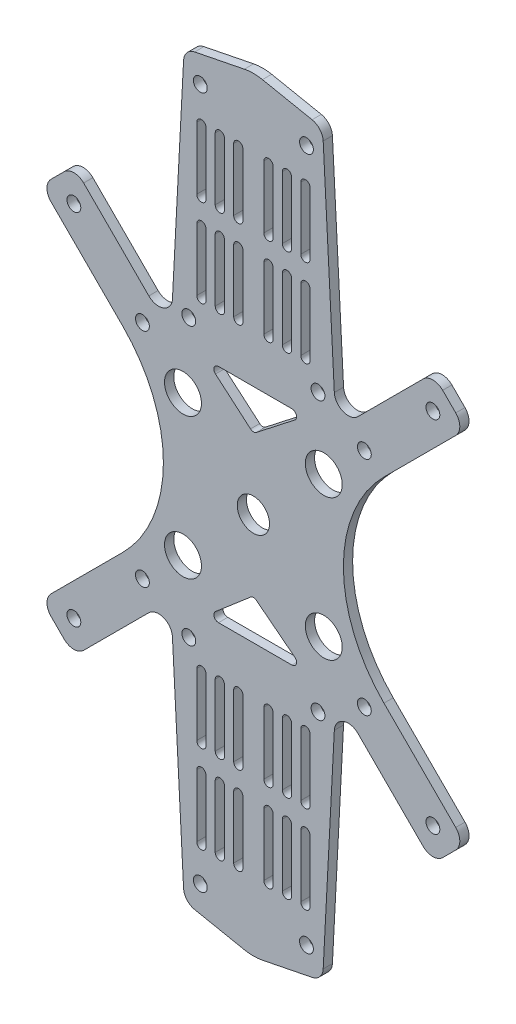
SolidWorks part; units mm, degrees
ref_plane "Alzado" through (0, 0, 0) normal (0, 0, 1) x (1, 0, 0)
ref_plane "Planta" through (0, 0, 0) normal (0, 1, 0) x (1, 0, 0)
ref_plane "Vista lateral" through (0, 0, 0) normal (1, 0, 0) x (0, 0, -1)
sketch "Croquis1" plane through (0, 0, 0) normal (0, 0, 1) x (1, 0, 0)
  line L0 (0, 0) -> (27.8544, 27.8544) construction
  line L1 (0, 0) -> (-42.4264, 42.4264) construction
  line L2 (0, 0) -> (0, 42.4264) construction
  line L3 (15.25, -15.25) -> (-15.25, -15.25) construction
  line L4 (15.25, -15.25) -> (15.25, 15.25) construction
  line L5 (15.25, 15.25) -> (-15.25, 15.25) construction
  line L6 (-15.25, -15.25) -> (-15.25, 15.25) construction
  line L7 (15.25, -15.25) -> (-15.25, 15.25) construction
  line L8 (15.25, 15.25) -> (-15.25, -15.25) construction
  line L9 (0, 42.4264) -> (-20, 42.4264) construction
  line L10 (-42.4264, 42.4264) -> (-38.8909, 45.9619)
  line L11 (-38.8909, 45.9619) -> (-31.0962, 38.1673)
  line L13 (-42.4264, 42.4264) -> (-45.9619, 38.8909)
  line L14 (-45.9619, 38.8909) -> (-38.1673, 31.0962)
  line L16 (38.8909, 45.9619) -> (31.0962, 38.1673)
  line L17 (42.4264, 42.4264) -> (38.8909, 45.9619)
  line L18 (42.4264, 42.4264) -> (45.9619, 38.8909)
  line L19 (-45.9619, -38.8909) -> (-38.1673, -31.0962)
  line L20 (0, 0) -> (-15.25, 0) construction
  line L21 (45.9619, 38.8909) -> (38.1673, 31.0962)
  line L22 (42.4264, -42.4264) -> (45.9619, -38.8909)
  line L23 (42.4264, -42.4264) -> (38.8909, -45.9619)
  line L24 (38.8909, -45.9619) -> (31.0962, -38.1673)
  line L27 (-38.8909, -45.9619) -> (-31.0962, -38.1673)
  line L28 (-42.4264, -42.4264) -> (-38.8909, -45.9619)
  line L29 (-42.4264, -42.4264) -> (-45.9619, -38.8909)
  line L30 (45.9619, -38.8909) -> (38.1673, -31.0962)
  line L31 (-15, 80) -> (15, 80) construction
  line L32 (0, -15.25) -> (0, -80) construction
  line L36 (-15, -80) -> (15, -80) construction
  line L41 (-12.268, -54) -> (-12.268, -67.5)
  line L43 (-10.268, -54) -> (-10.268, -67.5)
  line L105 (0, -80) -> (0, -83) construction
  line L106 (-15, -80) -> (0, -83)
  line L127 (15, -80) -> (0, -83)
  line L131 (0, 80) -> (0, 83) construction
  line L132 (-15, 80) -> (15, 80) construction
  line L136 (15, 80) -> (0, 83)
  line L157 (-15, 80) -> (0, 83)
  line L160 (-14, 30) -> (-17.8891, 33.8891) construction
  line L161 (-31.0962, 38.1673) -> (-22.6531, 29.7242)
  line L162 (-17.5359, 31.6883) -> (-15, 80)
  line L163 (17.5359, 31.6883) -> (15, 80)
  line L164 (31.0962, 38.1673) -> (22.6531, 29.7242)
  line L165 (31.0962, -38.1673) -> (22.6531, -29.7242)
  line L166 (17.5359, -31.6883) -> (15, -80)
  line L167 (-17.5359, -31.6883) -> (-15, -80)
  line L168 (-31.0962, -38.1673) -> (-22.6531, -29.7242)
  line L169 (-8.268, -54) -> (-8.268, -67.5)
  line L170 (-6.268, -54) -> (-6.268, -67.5)
  line L171 (-4.268, -54) -> (-4.268, -67.5)
  line L172 (-2.268, -54) -> (-2.268, -67.5)
  line L173 (-8.268, -35) -> (-8.268, -48.5)
  line L174 (-6.268, -35) -> (-6.268, -48.5)
  line L175 (-4.268, -35) -> (-4.268, -48.5)
  line L176 (-2.268, -35) -> (-2.268, -48.5)
  line L177 (-12.268, -35) -> (-12.268, -48.5)
  line L178 (-10.268, -35) -> (-10.268, -48.5)
  line L179 (10.268, -35) -> (10.268, -48.5)
  line L180 (12.268, -35) -> (12.268, -48.5)
  line L181 (2.268, -35) -> (2.268, -48.5)
  line L182 (4.268, -35) -> (4.268, -48.5)
  line L183 (6.268, -35) -> (6.268, -48.5)
  line L184 (8.268, -35) -> (8.268, -48.5)
  line L185 (2.268, -54) -> (2.268, -67.5)
  line L186 (4.268, -54) -> (4.268, -67.5)
  line L187 (6.268, -54) -> (6.268, -67.5)
  line L188 (8.268, -54) -> (8.268, -67.5)
  line L189 (10.268, -54) -> (10.268, -67.5)
  line L190 (12.268, -54) -> (12.268, -67.5)
  line L191 (12.268, 54) -> (12.268, 67.5)
  line L192 (10.268, 54) -> (10.268, 67.5)
  line L193 (8.268, 54) -> (8.268, 67.5)
  line L194 (6.268, 54) -> (6.268, 67.5)
  line L195 (4.268, 54) -> (4.268, 67.5)
  line L196 (2.268, 54) -> (2.268, 67.5)
  line L197 (8.268, 35) -> (8.268, 48.5)
  line L198 (6.268, 35) -> (6.268, 48.5)
  line L199 (4.268, 35) -> (4.268, 48.5)
  line L200 (2.268, 35) -> (2.268, 48.5)
  line L201 (12.268, 35) -> (12.268, 48.5)
  line L202 (10.268, 35) -> (10.268, 48.5)
  line L203 (-10.268, 35) -> (-10.268, 48.5)
  line L204 (-12.268, 35) -> (-12.268, 48.5)
  line L205 (-2.268, 35) -> (-2.268, 48.5)
  line L206 (-4.268, 35) -> (-4.268, 48.5)
  line L207 (-6.268, 35) -> (-6.268, 48.5)
  line L208 (-8.268, 35) -> (-8.268, 48.5)
  line L209 (-2.268, 54) -> (-2.268, 67.5)
  line L210 (-4.268, 54) -> (-4.268, 67.5)
  line L211 (-6.268, 54) -> (-6.268, 67.5)
  line L212 (-8.268, 54) -> (-8.268, 67.5)
  line L213 (-10.268, 54) -> (-10.268, 67.5)
  line L214 (-12.268, 54) -> (-12.268, 67.5)
  line L215 (-0.621, -15.7817) -> (-8.2129, -22.282)
  line L216 (-7.5625, -24.0416) -> (8.3607, -24.0416)
  line L217 (8.9758, -22.2532) -> (0.6445, -15.7529)
  line L218 (-7.5625, 24.0416) -> (8.3607, 24.0416)
  line L219 (8.9758, 22.2532) -> (0.6445, 15.7529)
  line L220 (-0.621, 15.7817) -> (-8.2129, 22.282)
  line L221 (-38.1673, 31.0962) -> (-28.2843, 21.2132)
  line L222 (-28.2843, -21.2132) -> (-38.1673, -31.0962)
  line L223 (28.2843, -21.2132) -> (38.1673, -31.0962)
  line L224 (38.1673, 31.0962) -> (28.2843, 21.2132)
  circle A0 centre (-15.25, 15.25) radius 4
  circle A1 centre (-24.0416, 24.0416) radius 1.5
  circle A2 centre (-38.8909, 38.8909) radius 1.5
  circle A5 centre (38.8909, 38.8909) radius 1.5
  circle A6 centre (24.0416, 24.0416) radius 1.5
  circle A7 centre (15.25, 15.25) radius 4
  circle A8 centre (15.25, -15.25) radius 4
  circle A9 centre (24.0416, -24.0416) radius 1.5
  circle A10 centre (38.8909, -38.8909) radius 1.5
  circle A12 centre (-15.25, -15.25) radius 4
  circle A13 centre (-24.0416, -24.0416) radius 1.5
  circle A14 centre (-38.8909, -38.8909) radius 1.5
  circle A18 centre (0, 0) radius 3.5
  circle A19 centre (-11.5, -75) radius 1.5
  circle A21 centre (-14, 30) radius 1.5
  arc A27 (-12.268, -54) -> (-10.268, -54) centre (-11.268, -54) cw
  arc A28 (-12.268, -67.5) -> (-10.268, -67.5) centre (-11.268, -67.5) ccw
  circle A111 centre (11.5, -75) radius 1.5
  circle A112 centre (11.5, 75) radius 1.5
  circle A137 centre (-11.5, 75) radius 1.5
  arc A138 (-22.6531, 29.7242) -> (-17.5359, 31.6883) centre (-20.5318, 31.8455) ccw
  arc A139 (22.6531, 29.7242) -> (17.5359, 31.6883) centre (20.5318, 31.8455) cw
  arc A140 (22.6531, -29.7242) -> (17.5359, -31.6883) centre (20.5318, -31.8455) ccw
  arc A141 (-22.6531, -29.7242) -> (-17.5359, -31.6883) centre (-20.5318, -31.8455) cw
  circle A142 centre (14, 30) radius 1.5
  circle A143 centre (14, -30) radius 1.5
  circle A144 centre (-14, -30) radius 1.5
  arc A145 (-8.268, -67.5) -> (-6.268, -67.5) centre (-7.268, -67.5) ccw
  arc A146 (-8.268, -54) -> (-6.268, -54) centre (-7.268, -54) cw
  arc A147 (-4.268, -67.5) -> (-2.268, -67.5) centre (-3.268, -67.5) ccw
  arc A148 (-4.268, -54) -> (-2.268, -54) centre (-3.268, -54) cw
  arc A149 (-8.268, -48.5) -> (-6.268, -48.5) centre (-7.268, -48.5) ccw
  arc A150 (-8.268, -35) -> (-6.268, -35) centre (-7.268, -35) cw
  arc A151 (-4.268, -48.5) -> (-2.268, -48.5) centre (-3.268, -48.5) ccw
  arc A152 (-4.268, -35) -> (-2.268, -35) centre (-3.268, -35) cw
  arc A153 (-12.268, -48.5) -> (-10.268, -48.5) centre (-11.268, -48.5) ccw
  arc A154 (-12.268, -35) -> (-10.268, -35) centre (-11.268, -35) cw
  arc A155 (12.268, -35) -> (10.268, -35) centre (11.268, -35) ccw
  arc A156 (12.268, -48.5) -> (10.268, -48.5) centre (11.268, -48.5) cw
  arc A157 (4.268, -35) -> (2.268, -35) centre (3.268, -35) ccw
  arc A158 (4.268, -48.5) -> (2.268, -48.5) centre (3.268, -48.5) cw
  arc A159 (8.268, -35) -> (6.268, -35) centre (7.268, -35) ccw
  arc A160 (8.268, -48.5) -> (6.268, -48.5) centre (7.268, -48.5) cw
  arc A161 (4.268, -54) -> (2.268, -54) centre (3.268, -54) ccw
  arc A162 (4.268, -67.5) -> (2.268, -67.5) centre (3.268, -67.5) cw
  arc A163 (8.268, -54) -> (6.268, -54) centre (7.268, -54) ccw
  arc A164 (8.268, -67.5) -> (6.268, -67.5) centre (7.268, -67.5) cw
  arc A165 (12.268, -67.5) -> (10.268, -67.5) centre (11.268, -67.5) cw
  arc A166 (12.268, -54) -> (10.268, -54) centre (11.268, -54) ccw
  arc A167 (12.268, 54) -> (10.268, 54) centre (11.268, 54) cw
  arc A168 (12.268, 67.5) -> (10.268, 67.5) centre (11.268, 67.5) ccw
  arc A169 (8.268, 67.5) -> (6.268, 67.5) centre (7.268, 67.5) ccw
  arc A170 (8.268, 54) -> (6.268, 54) centre (7.268, 54) cw
  arc A171 (4.268, 67.5) -> (2.268, 67.5) centre (3.268, 67.5) ccw
  arc A172 (4.268, 54) -> (2.268, 54) centre (3.268, 54) cw
  arc A173 (8.268, 48.5) -> (6.268, 48.5) centre (7.268, 48.5) ccw
  arc A174 (8.268, 35) -> (6.268, 35) centre (7.268, 35) cw
  arc A175 (4.268, 48.5) -> (2.268, 48.5) centre (3.268, 48.5) ccw
  arc A176 (4.268, 35) -> (2.268, 35) centre (3.268, 35) cw
  arc A177 (12.268, 48.5) -> (10.268, 48.5) centre (11.268, 48.5) ccw
  arc A178 (12.268, 35) -> (10.268, 35) centre (11.268, 35) cw
  arc A179 (-12.268, 35) -> (-10.268, 35) centre (-11.268, 35) ccw
  arc A180 (-12.268, 48.5) -> (-10.268, 48.5) centre (-11.268, 48.5) cw
  arc A181 (-4.268, 35) -> (-2.268, 35) centre (-3.268, 35) ccw
  arc A182 (-4.268, 48.5) -> (-2.268, 48.5) centre (-3.268, 48.5) cw
  arc A183 (-8.268, 35) -> (-6.268, 35) centre (-7.268, 35) ccw
  arc A184 (-8.268, 48.5) -> (-6.268, 48.5) centre (-7.268, 48.5) cw
  arc A185 (-4.268, 54) -> (-2.268, 54) centre (-3.268, 54) ccw
  arc A186 (-4.268, 67.5) -> (-2.268, 67.5) centre (-3.268, 67.5) cw
  arc A187 (-8.268, 54) -> (-6.268, 54) centre (-7.268, 54) ccw
  arc A188 (-8.268, 67.5) -> (-6.268, 67.5) centre (-7.268, 67.5) cw
  arc A189 (-12.268, 67.5) -> (-10.268, 67.5) centre (-11.268, 67.5) cw
  arc A190 (-12.268, 54) -> (-10.268, 54) centre (-11.268, 54) ccw
  arc A191 (8.3607, -24.0416) -> (8.9758, -22.2532) centre (8.3607, -23.0416) ccw
  arc A192 (0.6445, -15.7529) -> (-0.621, -15.7817) centre (0.0294, -16.5413) ccw
  arc A193 (-8.2129, -22.282) -> (-7.5625, -24.0416) centre (-7.5625, -23.0416) ccw
  arc A194 (8.3607, 24.0416) -> (8.9758, 22.2532) centre (8.3607, 23.0416) cw
  arc A195 (0.6445, 15.7529) -> (-0.621, 15.7817) centre (0.0294, 16.5413) cw
  arc A196 (-8.2129, 22.282) -> (-7.5625, 24.0416) centre (-7.5625, 23.0416) cw
  arc A197 (-28.2843, 21.2132) -> (-28.2843, -21.2132) centre (-49.4975, 0) cw
  arc A198 (28.2843, 21.2132) -> (28.2843, -21.2132) centre (49.4975, 0) ccw
  point P35 (-34.9935, 42.0646)
  point P37 (44.1942, 40.6586)
  point P45 (44.1942, -40.6586)
  point P52 (-16.268, -55.8441)
  point P61 (-34.9935, -42.0646)
  point P70 (0, 80)
  point P260 (-7.0711, 0)
  dimension "D2" = 8
  dimension "D4" = 5
  dimension "D8" = 14.75
  dimension "D10" = 3
  dimension "D11" = 3
  dimension "D13" = 11.5
  dimension "D15" = 3
  dimension "D16" = 14
  dimension "D18" = 3
  dimension "D24" = 3
  dimension "D26" = 1
  dimension "D27" = 7
  dimension "D28" = 30
  dimension "D1" = 30.5
  dimension "D3" = 60
  dimension "D5" = 21
  dimension "D6" = 15
  dimension "D7" = 5
  dimension "D9" = 5
  dimension "D12" = 80
  dimension "D14" = 5
  dimension "D17" = 4
  dimension "D19" = 2
  dimension "D20" = 13.5
  dimension "D21" = 7.5
  dimension "D22" = 3
  dimension "D25" = 2
  dimension "D23" = 5.5
extrude "Saliente-Extruir1" add sketch "Croquis1" along normal blind 2
fillet "Redondeo1" radius 3 12 edges at (45.9619, -38.8909, 1) (38.8909, -45.9619, 1) (-45.9619, -38.8909, 1) (-38.8909, -45.9619, 1) (45.9619, 38.8909, 1) (38.8909, 45.9619, 1) (-38.8909, 45.9619, 1) (-45.9619, 38.8909, 1) (15, 80, 1) (-15, 80, 1) (15, -80, 1) (-15, -80, 1)
fillet "Redondeo2" radius 10 2 edges at (0, -83, 1) (0, 83, 1)
